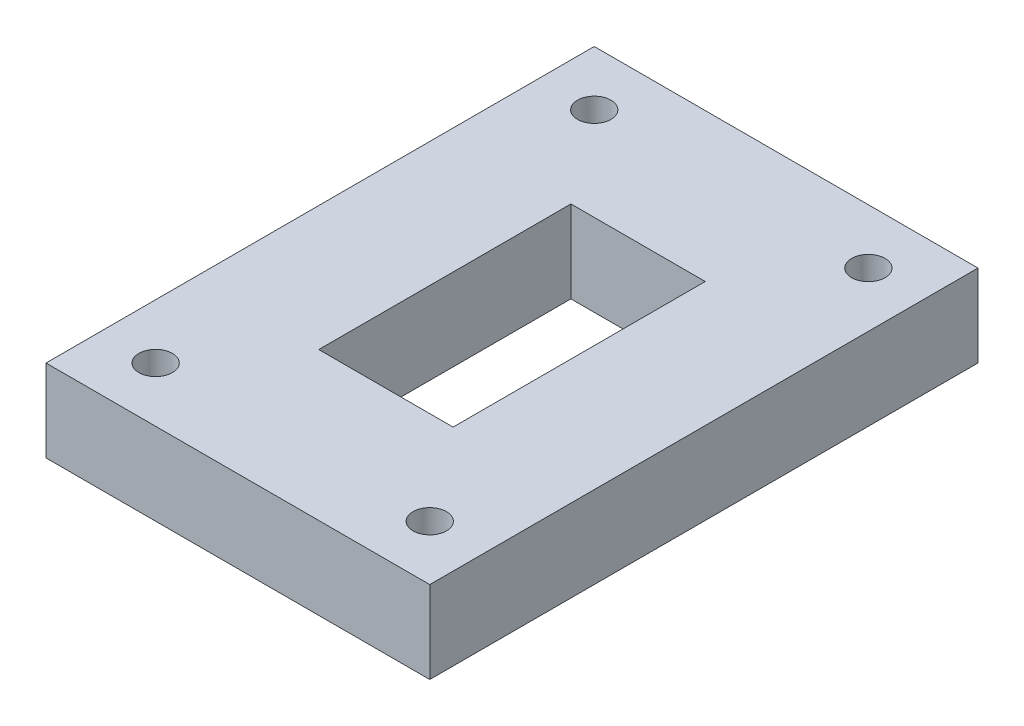
SolidWorks part; units mm, degrees
ref_plane "前视基准面" through (0, 0, 0) normal (0, 0, 1) x (1, 0, 0)
ref_plane "上视基准面" through (0, 0, 0) normal (0, 1, 0) x (1, 0, 0)
ref_plane "右视基准面" through (0, 0, 0) normal (1, 0, 0) x (0, 0, -1)
sketch "草图1" plane through (0, 0, 0) normal (0, 1, 0) x (1, 0, 0)
  line L0 (17.5, 0) -> (17.5, -50) construction
  line L1 (0, 0) -> (35, 0)
  line L2 (0, 0) -> (0, -50)
  line L3 (0, -50) -> (35, -50)
  line L4 (35, 0) -> (35, -50)
  line L5 (0, -25) -> (35, -25) construction
  line L7 (11.375, -13.5) -> (23.625, -13.5)
  line L8 (11.375, -13.5) -> (11.375, -36.5)
  line L9 (11.375, -36.5) -> (23.625, -36.5)
  line L10 (23.625, -13.5) -> (23.625, -36.5)
  line L11 (11.375, -13.5) -> (23.625, -36.5) construction
  line L12 (11.375, -36.5) -> (23.625, -13.5) construction
  point P9 (17.5, -25)
  dimension "D1" = 35
  dimension "D2" = 50
  dimension "D3" = 23
  dimension "D4" = 12.25
extrude "凸台-拉伸2" add sketch "草图1" against normal blind 7.5
sketch "草图2" plane through (0, -7.5, 0) normal (0, -1, 0) x (1, 0, 0)
  line L0 (35, 25) -> (0, 25) construction
  line L1 (35, 50) -> (35, 0) construction
  line L2 (0, 0) -> (0, 50) construction
  line L3 (17.5, 0) -> (17.5, 50) construction
  line L4 (35, 0) -> (0, 0) construction
  line L5 (0, 50) -> (35, 50) construction
  line L6 (35, 5) -> (0, 5) construction
  line L7 (5, 0) -> (5, 50) construction
  circle A0 centre (5, 5) radius 1.525
  circle A1 centre (5, 45) radius 1.525
  circle A2 centre (30, 45) radius 1.525
  circle A3 centre (30, 5) radius 1.525
  dimension "D3" = 3.05
  dimension "D1" = 5
  dimension "D2" = 5
extrude "切除-拉伸1" cut sketch "草图2" against normal through all
